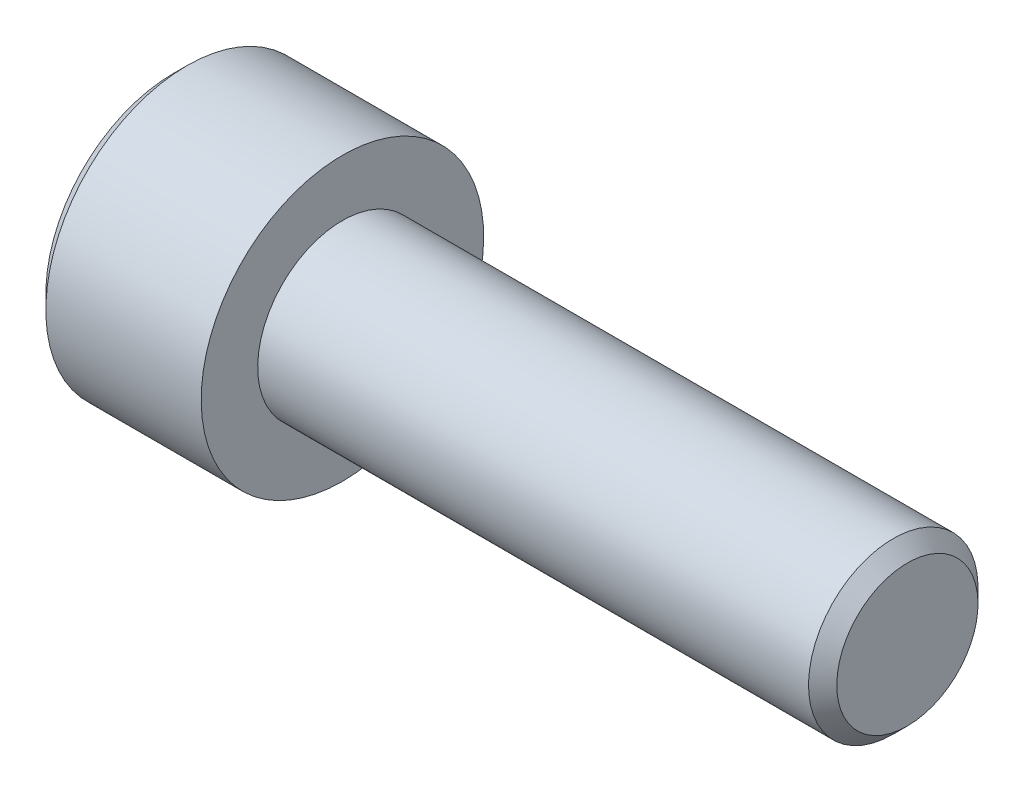
SolidWorks part; units mm, degrees
ref_plane "Front" through (0, 0, 0) normal (0, 0, 1) x (1, 0, 0)
ref_plane "Top" through (0, 0, 0) normal (0, 1, 0) x (1, 0, 0)
ref_plane "Right" through (0, 0, 0) normal (1, 0, 0) x (0, 0, -1)
sketch "Sketch1" plane through (0, 0, 0) normal (0, 0, 1) x (1, 0, 0)
  line L0 (-6, 0) -> (-6, 5)
  line L1 (-6, 0) -> (20, 0)
  line L2 (-6, 5) -> (0, 5)
  line L3 (0, 5) -> (0, 3)
  line L4 (0, 3) -> (20, 3)
  line L6 (20, 3) -> (20, 0)
  line L8 (20, 0) -> (-6, 0) construction
  dimension "D1" = 6
  dimension "D2" = 10
  dimension "D3" = 6
  dimension "D4" = 20
revolve "Revolve1" add sketch "Sketch1" angle 360 about L8
sketch "Sketch2" plane through (0, 0, 0) normal (0, 0, 1) x (1, 0, 0)
  line L0 (-6, 0) -> (-6, 2.495)
  line L1 (-6, 2.495) -> (-3, 2.495)
  line L2 (-3, 2.495) -> (-2.3315, 0)
  line L3 (-6, 0) -> (-2.3315, 0)
  line L4 (-2.3315, 0) -> (-6, 0) construction
  line L6 (-6, 5) -> (-6, -5) construction
  dimension "D1" = 4.99
  dimension "D2" = 75
  dimension "D3" = 3
revolve "Cut-Revolve1" cut sketch "Sketch2" angle 360 about L4
sketch "Sketch3" plane through (-6, 0, 0) normal (-1, 0, 0) x (0, 0, 1)
  line L1 (0, 2.8868) -> (-2.5, 1.4434)
  line L2 (-2.5, 1.4434) -> (-2.5, -1.4434)
  line L3 (-2.5, -1.4434) -> (0, -2.8868)
  line L4 (0, -2.8868) -> (2.5, -1.4434)
  line L5 (2.5, -1.4434) -> (2.5, 1.4434)
  line L6 (2.5, 1.4434) -> (0, 2.8868)
  circle A0 centre (0, 0) radius 2.5 construction
  dimension "D1" = 5
extrude "Cut-Extrude1" cut sketch "Sketch3" against normal blind 3
chamfer "Chamfer1" distance 0.5 angle 45 2 edges at (20, -3, 0) (-6, -5, 0)
